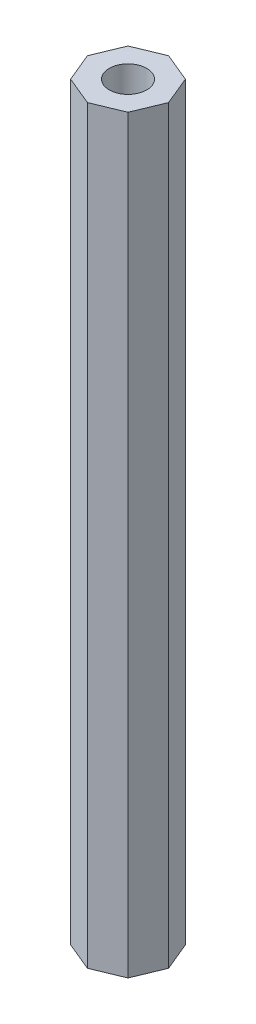
SolidWorks part; units mm, degrees
ref_plane "Front" through (0, 0, 0) normal (0, 0, 1) x (1, 0, 0)
ref_plane "Top" through (0, 0, 0) normal (0, 1, 0) x (1, 0, 0)
ref_plane "Right" through (0, 0, 0) normal (1, 0, 0) x (0, 0, -1)
sketch "Sketch1" plane through (0, 0, 0) normal (0, 1, 0) x (1, 0, 0)
  line L1 (1.6236, 0) -> (1.1481, 1.1481)
  line L2 (1.1481, 1.1481) -> (0, 1.6236)
  line L3 (0, 1.6236) -> (-1.1481, 1.1481)
  line L4 (-1.1481, 1.1481) -> (-1.6236, 0)
  line L5 (-1.6236, 0) -> (-1.1481, -1.1481)
  line L6 (-1.1481, -1.1481) -> (0, -1.6236)
  line L7 (0, -1.6236) -> (1.1481, -1.1481)
  line L8 (1.1481, -1.1481) -> (1.6236, 0)
  circle A0 centre (0, 0) radius 1.5 construction
  circle A1 centre (0, 0) radius 0.75
extrude "Boss-Extrude1" add sketch "Sketch1" along normal blind 30
